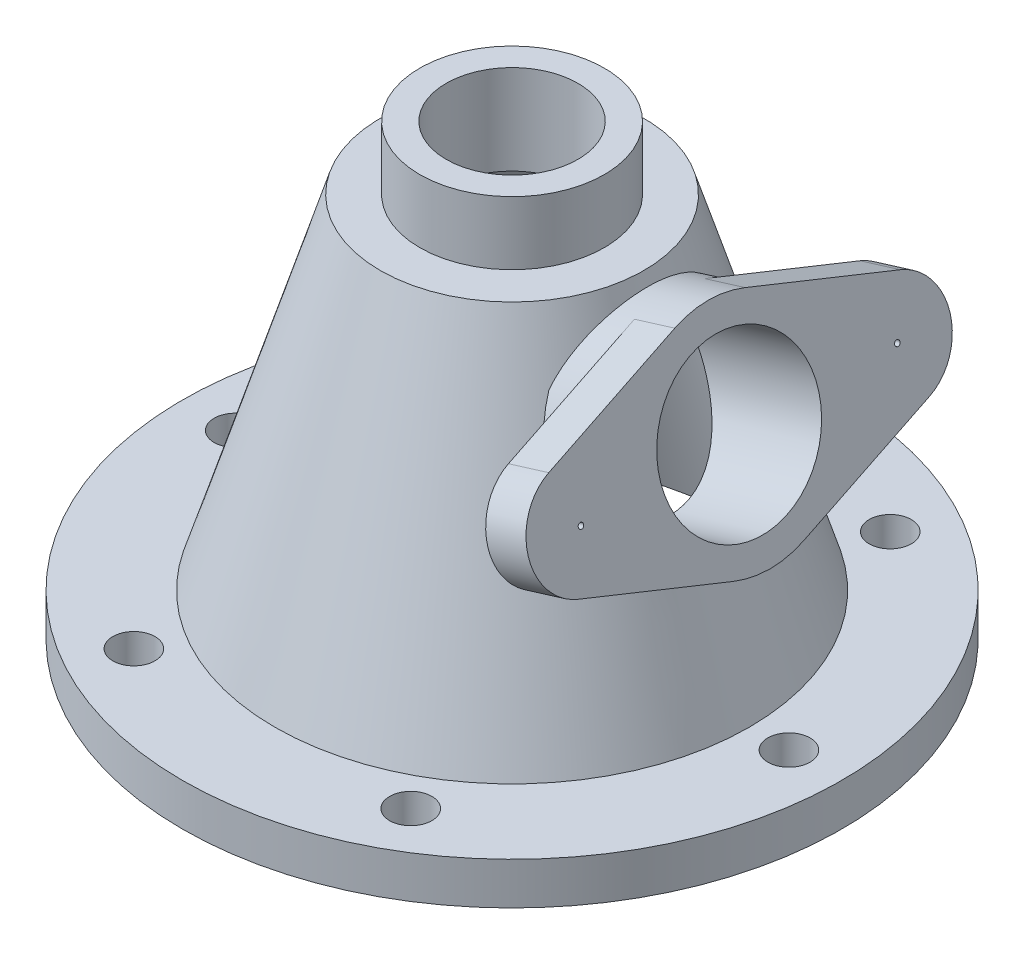
SolidWorks part; units mm, degrees
ref_plane "前视基准面" through (0, 0, 0) normal (0, 0, 1) x (1, 0, 0)
ref_plane "上视基准面" through (0, 0, 0) normal (0, 1, 0) x (1, 0, 0)
ref_plane "右视基准面" through (0, 0, 0) normal (1, 0, 0) x (0, 0, -1)
sketch "草图1" plane through (0, 0, 0) normal (0, 1, 0) x (1, 0, 0)
  circle A0 centre (0, 0) radius 45
  circle A1 centre (0, 0) radius 62.5
extrude "凸台-拉伸2" add sketch "草图1" along normal blind 8
sketch "草图3" plane through (0, 0, 0) normal (0, 1, 0) x (1, 0, 0)
  circle A0 centre (0, 0) radius 52.5
  circle A1 centre (-52.5, 0) radius 4
  circle A2 centre (-26.25, 45.4663) radius 4
  circle A3 centre (26.25, 45.4663) radius 4
  circle A4 centre (52.5, 0) radius 4
  circle A5 centre (26.25, -45.4663) radius 4
  circle A6 centre (-26.25, -45.4663) radius 4
  point P17 (0, 0)
  dimension "D1" = 6
extrude "切除-拉伸1" cut sketch "草图3" along normal blind 8 contours A0 A2 | A0 A2 | A0 A3 | A0 A3 | A0 A4 | A0 A4 | A0 A5 | A0 A5 | A0 A6 | A0 A6 | A0 A1 | A0 A1
ref_axis "基准轴1" through (0, 89.25, 0) along (0, -1, 0)
sketch "草图7" plane through (0, 0, 0) normal (0, 0, 1) x (1, 0, 0)
  line L2 (-25, 73) -> (-47.4615, 0)
  line L3 (-62.5, 0) -> (62.5, 0) construction
  line L4 (-47.4615, 0) -> (-40.9231, 0)
  line L5 (-40.9231, 0) -> (-20, 68)
  line L6 (-20, 68) -> (-12.5, 68)
  line L7 (-17.5, 73) -> (-25, 73)
  line L10 (-12.5, 73) -> (-12.5, 68)
  line L11 (-12.5, 73) -> (-12.5, 85)
  line L12 (-12.5, 85) -> (-17.5, 85)
  line L13 (-17.5, 85) -> (-17.5, 73)
  line L16 (-17.5, 68) -> (-12.5, 68)
  dimension "D5" = 5
  dimension "D6" = 12
revolve "旋转5" add sketch "草图7" angle 360 about axis through (0, 89.25, 0) along (0, -1, 0)
ref_plane "基准面1" through (43.3568, 13.3405, 0) normal (0.9558, 0.2941, 0) x (0, 0, -1)
sketch "草图8" plane through (43.3568, 13.3405, 0) normal (0.9558, 0.2941, 0) x (0, 0, -1)
  line L0 (0, 85.3033) -> (0, -4.0621) construction
  circle A0 centre (0, 40) radius 20
extrude "凸台-拉伸3" add sketch "草图8" along normal blind 12 and the other way blind 5
ref_plane "基准面2" through (54.8261, 16.8696, 0) normal (0.9558, 0.2941, 0) x (0, 0, -1)
sketch "草图9" plane through (54.8261, 16.8696, 0) normal (0.9558, 0.2941, 0) x (0, 0, -1)
  line L0 (0, 85.3033) -> (0, -4.0621) construction
  line L1 (-33.3333, 49.4281) -> (-6.6667, 58.8562)
  line L2 (-33.3333, 30.5719) -> (-6.6667, 21.1438)
  line L3 (33.3333, 49.4281) -> (6.6667, 58.8562)
  line L4 (33.3333, 30.5719) -> (6.6667, 21.1438)
  arc A0 (-6.6667, 21.1438) -> (6.6667, 21.1438) centre (0, 40) ccw
  arc A1 (33.3333, 30.5719) -> (33.3333, 49.4281) centre (30, 40) ccw
  arc A2 (-33.3333, 49.4281) -> (-33.3333, 30.5719) centre (-30, 40) ccw
  circle A3 centre (-30, 40) radius 0.5
  circle A4 centre (30, 40) radius 0.5
  arc A5 (6.6667, 58.8562) -> (-6.6667, 58.8562) centre (0, 40) ccw
extrude "凸台-拉伸4" add sketch "草图9" against normal blind 8
sketch "草图10" plane through (54.8261, 16.8696, 0) normal (0.9558, 0.2941, 0) x (0, 0, -1)
  line L0 (0, 85.3033) -> (0, -4.0621) construction
  circle A0 centre (0, 40) radius 15
extrude "切除-拉伸2" cut sketch "草图10" against normal blind 25
